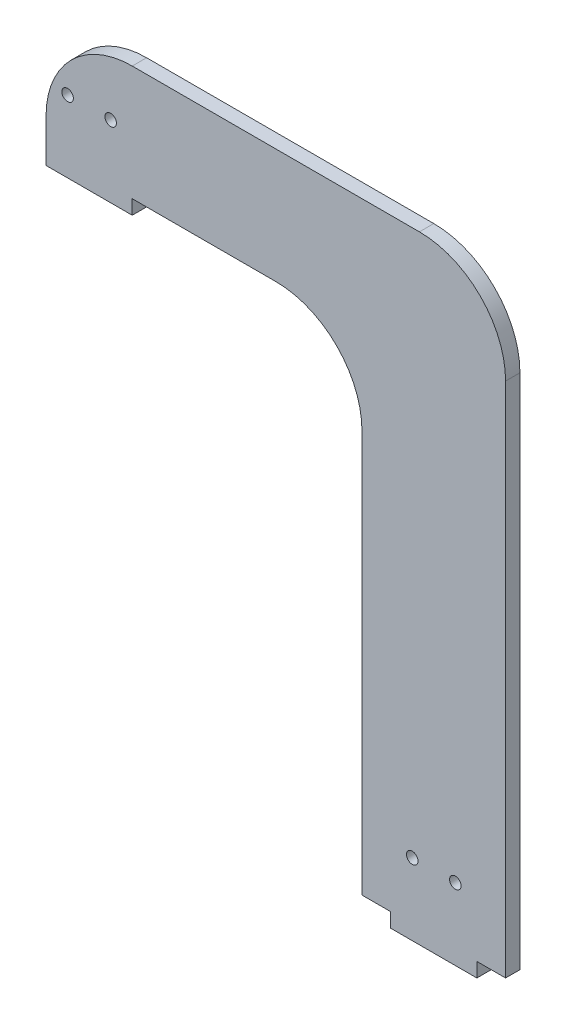
SolidWorks part; units mm, degrees
ref_plane "Alzado" through (0, 0, 0) normal (0, 0, 1) x (1, 0, 0)
ref_plane "Planta" through (0, 0, 0) normal (0, 1, 0) x (1, 0, 0)
ref_plane "Vista lateral" through (0, 0, 0) normal (1, 0, 0) x (0, 0, -1)
sketch "Croquis1" plane through (0, 0, 0) normal (0, 0, 1) x (1, 0, 0)
  line L0 (-30, 0) -> (0, 0)
  line L1 (0, 0) -> (0, 5)
  line L2 (0, 5) -> (10, 5)
  line L3 (-30, 0) -> (-30, 5)
  line L4 (-30, 5) -> (-40, 5)
  line L5 (-40, 5) -> (-40, 175)
  line L6 (-40, 175) -> (-120, 175)
  line L7 (10, 5) -> (10, 215)
  line L8 (10, 215) -> (-150, 215)
  line L9 (-120, 175) -> (-120, 170)
  line L10 (-120, 170) -> (-150, 170)
  line L11 (-150, 170) -> (-150, 215)
  dimension "D1" = 30
  dimension "D2" = 5
  dimension "D3" = 10
  dimension "D4" = 40
  dimension "D5" = 175
  dimension "D6" = 80
  dimension "D7" = 30
  dimension "D8" = 5
extrude "Saliente-Extruir1" add sketch "Croquis1" along normal blind 5
fillet "Redondeo1" radius 30 3 edges at (10, 215, 2.5) (-40, 175, 2.5) (-150, 215, 2.5)
sketch "Croquis2" plane through (0, 0, 5) normal (0, 0, 1) x (1, 0, 0)
  line L1 (0, 5) -> (10, 5) construction
  line L2 (0, 0) -> (0, 5) construction
  line L3 (-15, 0) -> (-15, 23.1031) construction
  line L4 (-30, 0) -> (0, 0) construction
  line L5 (-120, 175) -> (-70, 175) construction
  line L6 (-120, 170) -> (-120, 175) construction
  line L7 (-135, 170) -> (-135, 188.2835) construction
  line L8 (-150, 170) -> (-120, 170) construction
  circle A0 centre (-7.5, 25) radius 2
  circle A1 centre (-22.5, 25) radius 2
  circle A2 centre (-127.5, 195) radius 2
  circle A3 centre (-142.5, 195) radius 2
  dimension "D1" = 4
  dimension "D4" = 20
  dimension "D2" = 20
  dimension "D3" = 7.5
  dimension "D5" = 7.5
extrude "Cortar-Extruir1" cut sketch "Croquis2" against normal up to next
